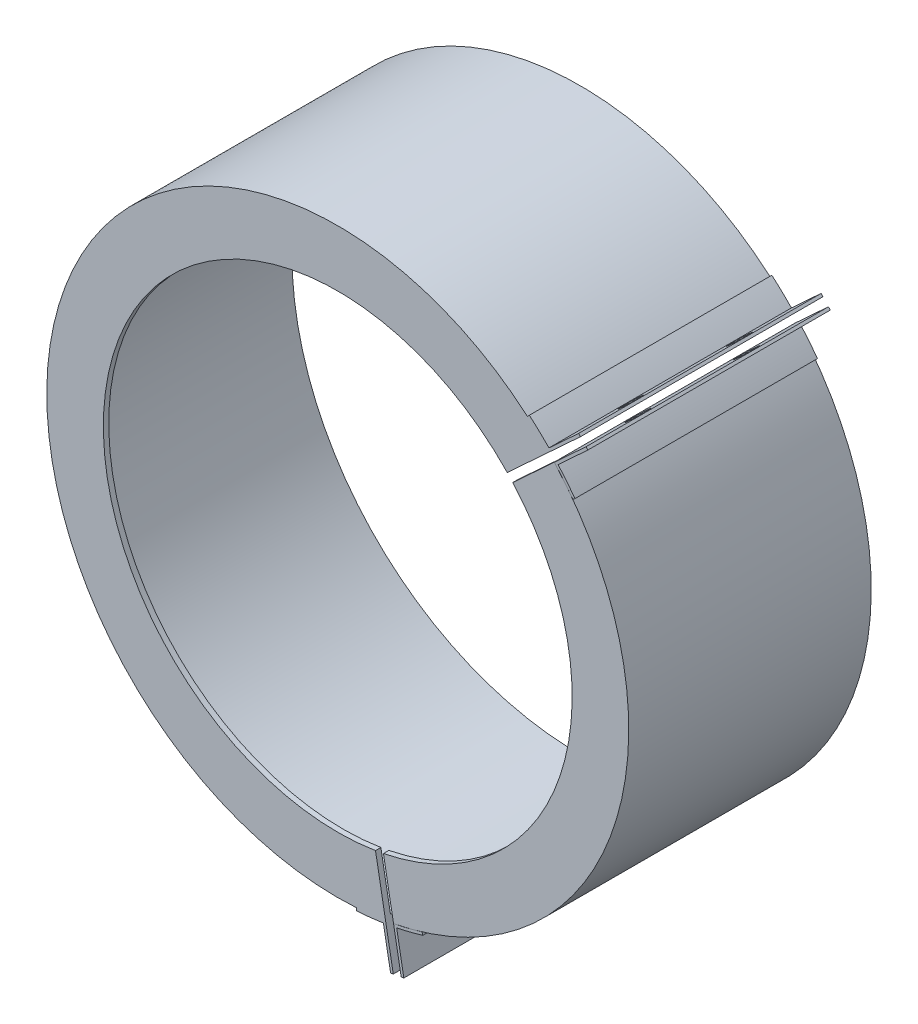
SolidWorks part; units mm, degrees
material "Alloy Steel"
ref_plane "Front Plane" through (0, 0, 0) normal (0, 0, 1) x (1, 0, 0)
ref_plane "Top Plane" through (0, 0, 0) normal (0, 1, 0) x (1, 0, 0)
ref_plane "Right Plane" through (0, 0, 0) normal (1, 0, 0) x (0, 0, -1)
sketch "Sketch1" plane through (0, 0, 0) normal (0, 0, 1) x (1, 0, 0)
  line L0 (0, 0) -> (79.3589, 73.2541) construction
  line L2 (0, 0) -> (19.2234, -106.2754) construction
  line L5 (0, 0) -> (103.9749, 95.9764) construction
  line L6 (0, 0) -> (25.1863, -139.2404) construction
  circle A0 centre (0, 0) radius 104 construction
  circle A1 centre (0, 0) radius 107
  circle A2 centre (0, 0) radius 108
  dimension "D1" = 208
  dimension "D2" = 1
  dimension "D3" = 3
extrude "Boss-Extrude1" add sketch "Sketch1" along normal blind 90
sketch "Sketch5" plane through (0, 0, 90) normal (0, 0, 1) x (1, 0, 0)
  circle A0 centre (0, 0) radius 87
  circle A1 centre (0, 0) radius 107 construction
  circle A2 centre (0, 0) radius 107 construction
  circle M2 centre (0, 0) radius 107
  dimension "D1" = 20
extrude "Boss-Extrude2" add sketch "Sketch5" against normal blind 2 contours A0 M2
sketch "Sketch3" plane through (0, 0, 90) normal (0, 0, 1) x (1, 0, 0)
  line L0 (78.3415, 74.3563) -> (62.9011, 60.1037)
  line L1 (62.9011, 60.1037) -> (64.9359, 57.8993)
  line L2 (64.9359, 57.8993) -> (80.3763, 72.1519)
  line L3 (80.3763, 72.1519) -> (78.3415, 74.3563)
  line L4 (14.0072, -85.865) -> (17.7474, -106.5424)
  line L5 (17.7474, -106.5424) -> (20.6995, -106.0084)
  line L6 (20.6995, -106.0084) -> (16.9593, -85.331)
  line L7 (16.9593, -85.331) -> (14.0072, -85.865)
  line L8 (15.4832, -85.598) -> (19.2234, -106.2754)
  line L10 (63.9185, 59.0015) -> (79.3589, 73.2541)
  line L11 (0, 0) -> (19.2234, -106.2754) construction
  line L12 (0, 0) -> (79.3589, 73.2541) construction
  circle A0 centre (0, 0) radius 87 construction
  circle A1 centre (0, 0) radius 108 construction
  dimension "D1" = 3
extrude "Cut-Extrude1" cut sketch "Sketch3" against normal through all
ref_plane "Plane2" through (0, 0, 0) normal (0.6783, -0.7348, 0) x (0.7348, 0.6783, 0)
ref_plane "Plane3" through (0, 0, 0) normal (-0.984, -0.178, 0) x (0.178, -0.984, 0)
ref_plane "Plane4" through (0, 0, 0) normal (-0.3176, -0.9482, 0) x (0, 0, -1)
ref_plane "Plane5" through (0, 0, 45) normal (0, 0, 1) x (1, 0, 0)
sketch "Sketch6" plane through (0, 0, 0) normal (0, 0, 1) x (1, 0, 0)
  line L0 (78.3339, 74.3492) -> (90.0907, 85.2017)
  line L1 (90.0907, 85.2017) -> (89.4125, 85.9365)
  line L2 (89.4125, 85.9365) -> (78.377, 75.7499)
  line L3 (71.1049, 82.6141) -> (70.4526, 81.8562)
  line L4 (78.3339, 74.3492) -> (62.9011, 60.1037) construction
  line L5 (80.3687, 72.1448) -> (92.1256, 82.9973)
  line L6 (92.1256, 82.9973) -> (92.8038, 82.2625)
  line L7 (92.8038, 82.2625) -> (81.7684, 72.0759)
  line L8 (87.2221, 63.6891) -> (88.0298, 64.2788)
  line L10 (64.9359, 57.8993) -> (80.3687, 72.1448) construction
  line L12 (-84.382, 28.2647) -> (84.382, -28.2647) construction
  line L13 (20.6976, -105.9982) -> (23.5455, -121.7427)
  line L14 (23.5455, -121.7427) -> (24.5296, -121.5647)
  line L15 (24.5296, -121.5647) -> (21.8564, -106.7862)
  line L16 (31.2616, -103.3766) -> (31.551, -104.3338)
  line L17 (19.6094, -122.4546) -> (16.9363, -107.6762)
  line L18 (20.5935, -122.2766) -> (19.6094, -122.4546)
  line L19 (17.7455, -106.5321) -> (20.5935, -122.2766)
  line L20 (6.9968, -108.7752) -> (6.9326, -107.7773)
  arc A0 (78.3339, 74.3492) -> (70.4526, 81.8562) centre (0, 0) ccw
  arc A1 (78.377, 75.7499) -> (71.1049, 82.6141) centre (0, 0) ccw
  circle A2 centre (0, 0) radius 108 construction
  arc A3 (20.6976, -105.9982) -> (31.2616, -103.3766) centre (0, 0) ccw
  arc A4 (80.3687, 72.1448) -> (87.2221, 63.6891) centre (0, 0) cw
  arc A5 (81.7684, 72.0759) -> (88.0298, 64.2788) centre (0, 0) cw
  arc A6 (21.8564, -106.7862) -> (31.551, -104.3338) centre (0, 0) ccw
  arc A7 (16.9363, -107.6762) -> (6.9968, -108.7752) centre (0, 0) cw
  arc A8 (17.7455, -106.5321) -> (6.9326, -107.7773) centre (0, 0) cw
  dimension "D1" = 10
  dimension "D2" = 1
  dimension "D3" = 10
  dimension "D4" = 16
extrude "Boss-Extrude3" add sketch "Sketch6" along normal through all
sketch "Sketch7" plane through (-1.6957, 1.837, 0) normal (-0.6783, 0.7348, 0) x (0, 0, 1)
  line L0 (0, 123.9896) -> (0, 108.9713) construction
  line L1 (45, -102.4836) -> (45, 102.4836) construction
  circle A0 centre (24.8465, 116.4805) radius 4
  circle A2 centre (65.1535, 116.4805) radius 4
  point P4 (0, 116.4805)
  dimension "D1" = 8
extrude "Cut-Extrude2" cut sketch "Sketch7" against normal through all
mirror "Mirror4" about plane through (0, 0, 0) normal (-0.3176, -0.9482, 0) of "Cut-Extrude2"
